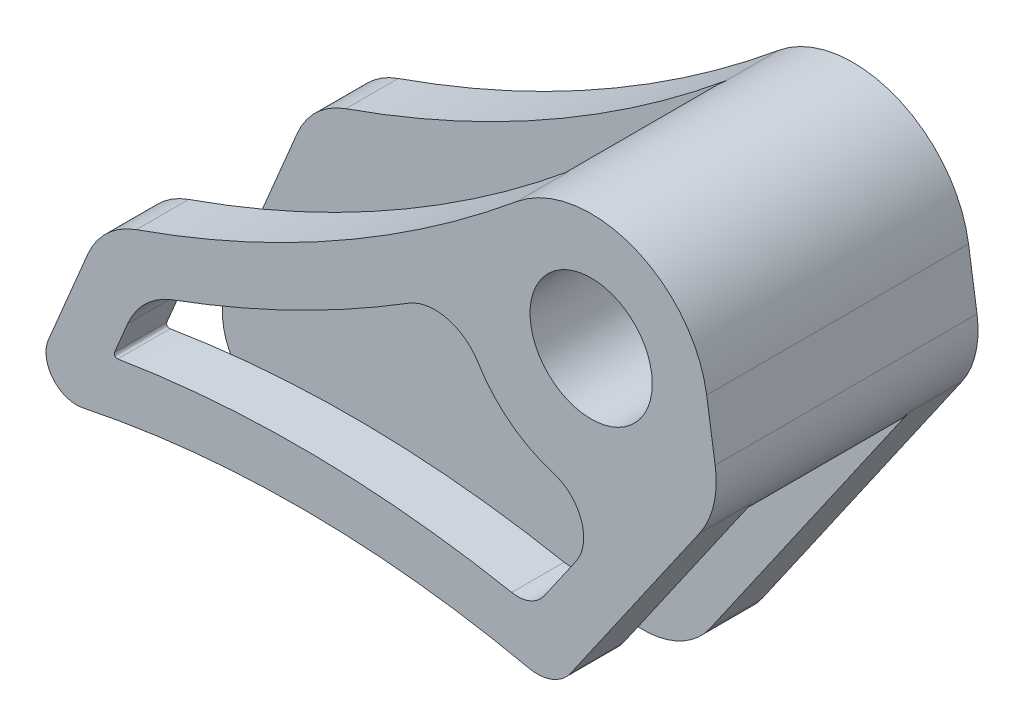
SolidWorks part; units mm, degrees
ref_plane "Front Plane" through (0, 0, 0) normal (0, 0, 1) x (1, 0, 0)
ref_plane "Top Plane" through (0, 0, 0) normal (0, 1, 0) x (1, 0, 0)
ref_plane "Right Plane" through (0, 0, 0) normal (1, 0, 0) x (0, 0, -1)
sketch "Sketch11" plane through (0, 0, 0) normal (0, 0, 1) x (1, 0, 0)
  circle A0 centre (0, 0) radius 60
  circle A1 centre (0, 0) radius 70
  ellipse E0 centre (0, 0) end of major axis (0, 70) minor radius 60
  dimension "D1" = 120
  dimension "D2" = 140
sketch "Sketch14" plane through (0, 0, 0) normal (0, 0, 1) x (1, 0, 0)
  line L0 (-351.4966, -91.4898) -> (-50.83, -91.4898) construction
  line L1 (-16.1614, 57.9773) -> (-12.1811, 67.465)
  line L2 (11.4756, 54.7519) -> (22.8728, 71.1675)
  line L3 (23.2736, 78.2138) -> (23.7603, 74.9796)
  arc A0 (-12.1811, 67.465) -> (-9.393, 70.0872) centre (-7.8417, 65.6445) cw
  arc A1 (-16.1614, 57.9773) -> (-11.866, 52.6316) centre (-12.565, 56.4685) ccw
  arc A2 (-11.866, 52.6316) -> (6.9008, 52.8103) centre (-1.9642, -1.7177) cw
  arc A3 (6.9008, 52.8103) -> (11.4756, 54.7519) centre (7.6485, 57.409) ccw
  arc A4 (-9.393, 70.0872) -> (12.3923, 82.3738) centre (-32.7321, 136.9266) ccw
  arc A5 (12.3923, 82.3738) -> (23.2736, 78.2138) centre (16.657, 77.218) cw
  arc A6 (23.7603, 74.9796) -> (22.8728, 71.1675) centre (18.5184, 74.1906) cw
extrude "Boss-Extrude1" add sketch "Sketch14" along normal blind 15
ref_plane "Plane1" through (0, 0, 7) normal (0, 0, -1) x (-1, 0, 0)
sketch "Sketch16" plane through (0, 0, 15) normal (0, 0, 1) x (1, 0, 0)
  line L0 (16.657, 77.218) -> (23.7603, 74.9796) construction
  line L2 (16.657, 77.218) -> (23.2736, 78.2138) construction
  line L3 (16.657, 77.218) -> (16.657, 88.7771) construction
  circle A0 centre (16.657, 77.218) radius 2.1
  arc A1 (23.2736, 78.2138) -> (12.3923, 82.3738) centre (16.657, 77.218) ccw construction
  dimension "D1" = 4.2
extrude "Cut-Extrude2" cut sketch "Sketch16" against normal through all
sketch "Sketch17" plane through (0, 0, 15) normal (0, 0, 1) x (1, 0, 0)
  circle A0 centre (16.657, 77.218) radius 3.5
  dimension "D1" = 7
extrude "Cut-Extrude3" cut sketch "Sketch17" against normal blind 5
sketch "Sketch15" plane through (0, 0, 7) normal (0, 0, 1) x (1, 0, 0)
  line L2 (13.7084, 83.2243) -> (11.9266, 87.4848)
  line L3 (11.9266, 87.4848) -> (-22.3317, 87.4848)
  line L4 (-22.3317, 87.4848) -> (-22.3317, 56.5662)
  line L5 (-22.3317, 56.5662) -> (-22.3317, 46.4789)
  line L6 (-22.3317, 46.4789) -> (13.1792, 46.4789)
  line L7 (13.1792, 46.4789) -> (31.8325, 71.1675)
  line L8 (31.8325, 71.1675) -> (22.8728, 71.1675)
  line L9 (15.4487, 69.869) -> (12.7822, 71.763)
  arc A0 (22.8728, 71.1675) -> (15.4487, 69.869) centre (18.5184, 74.1906) cw
  arc A3 (22.8728, 71.1675) -> (23.7603, 74.9796) centre (18.5184, 74.1906) ccw construction
  arc A6 (12.7822, 71.763) -> (13.7084, 83.2243) centre (16.657, 77.218) cw
  arc A8 (23.2736, 78.2138) -> (12.3923, 82.3738) centre (16.657, 77.218) ccw construction
  circle A9 centre (16.657, 77.218) radius 3.5 construction
  point P4 (-18.4077, 48.386)
  point P5 (31.8325, 71.1675)
  point P6 (11.9266, 90.061)
  point P7 (-18.7335, 84.9023)
  point P19 (11.9266, 87.4848)
  point P20 (-18.7335, 87.4848)
  point P21 (-22.3317, 46.4789)
  point P22 (13.7084, 83.2243)
extrude "Cut-Extrude1" cut sketch "Sketch15" against normal offset from surface 3 and the other way offset from surface (5 mm away) 3 up to face at (18.757, 77.218, 0) other way up to face at (20.157, 77.218, 15)
sketch "Sketch19" plane through (0, 0, 15) normal (0, 0, 1) x (1, 0, 0)
  line L1 (-12.1811, 67.465) -> (-16.1614, 57.9773) construction
  line L2 (11.4756, 54.7519) -> (22.8728, 71.1675) construction
  line L3 (-14.432, 62.0996) -> (-17.7483, 61.4236)
  line L4 (-17.7483, 61.4236) -> (-17.7483, 50.8455)
  line L5 (-17.7483, 50.8455) -> (18.7482, 50.8455)
  line L6 (18.7482, 50.8455) -> (18.7482, 60.531)
  line L7 (18.7482, 60.531) -> (15.488, 60.531)
  arc A0 (-14.432, 62.0996) -> (-12.4636, 59.7131) centre (-12.8207, 61.4236) ccw
  arc A1 (-12.4636, 59.7131) -> (13.0721, 59.5829) centre (0, 0) cw
  arc A2 (13.0721, 59.5829) -> (15.488, 60.531) centre (13.5719, 61.8613) ccw
  circle A4 centre (0, 0) radius 60 construction
  dimension "D1" = 1
extrude "Cut-Extrude5" cut sketch "Sketch19" against normal up to surface (3 mm away) up to face at (2.8875, 64.7441, 12)
sketch "Sketch18" plane through (0, 0, 15) normal (0, 0, 1) x (1, 0, 0)
  line L0 (-9.8824, 65.1894) -> (-10.6439, 63.3742)
  line L1 (13.9663, 63.5996) -> (15.7935, 66.2314)
  line L2 (15.488, 60.531) -> (22.8728, 71.1675) construction
  line L3 (-12.1811, 67.465) -> (-14.432, 62.0996) construction
  line L4 (-12.1811, 67.465) -> (-14.432, 62.0996) construction
  line L5 (15.488, 60.531) -> (22.8728, 71.1675) construction
  arc A0 (-10.6439, 63.3742) -> (-10.4585, 63.1397) centre (-10.4865, 63.3082) ccw
  arc A1 (-10.4585, 63.1397) -> (12.1105, 62.8437) centre (0, 0) cw
  arc A2 (12.1105, 62.8437) -> (13.9663, 63.5996) centre (12.458, 64.6468) ccw
  arc A5 (-9.393, 70.0872) -> (-12.1811, 67.465) centre (-7.8417, 65.6445) ccw construction
  circle A6 centre (16.657, 77.218) radius 3.5 construction
  arc A7 (10.1805, 73.2814) -> (14.4891, 69.9556) centre (16.657, 77.218) ccw
  arc A8 (14.4891, 69.9556) -> (15.7935, 66.2314) centre (13.7921, 67.6209) cw
  arc A10 (13.0721, 59.5829) -> (-12.4636, 59.7131) centre (0, 0) ccw construction
  arc A13 (-9.393, 70.0872) -> (12.3923, 82.3738) centre (-32.7321, 136.9266) ccw construction
  arc A14 (-9.8824, 65.1894) -> (-7.3111, 67.6462) centre (-5.7777, 63.4674) cw
  arc A15 (-7.3111, 67.6462) -> (6.1973, 74.2329) centre (-32.7321, 136.9266) ccw
  arc A16 (6.1973, 74.2329) -> (10.1805, 73.2814) centre (7.7177, 71.7843) cw
  arc A18 (-14.432, 62.0996) -> (-12.4636, 59.7131) centre (-12.8207, 61.4236) ccw construction
  arc A19 (13.0721, 59.5829) -> (15.488, 60.531) centre (13.5719, 61.8613) ccw construction
  point P11 (14.3541, 70.6877)
  point P15 (10.1805, 73.2814)
  dimension "D1" = 3
  dimension "D2" = 3
  dimension "D3" = 3
  dimension "D5" = 3
  dimension "D6" = 3
  dimension "D7" = 3
  dimension "D8" = 3
extrude "Cut-Extrude4" cut sketch "Sketch18" against normal up to surface (3 mm away) up to face at (4.0939, 67.2723, 12)
